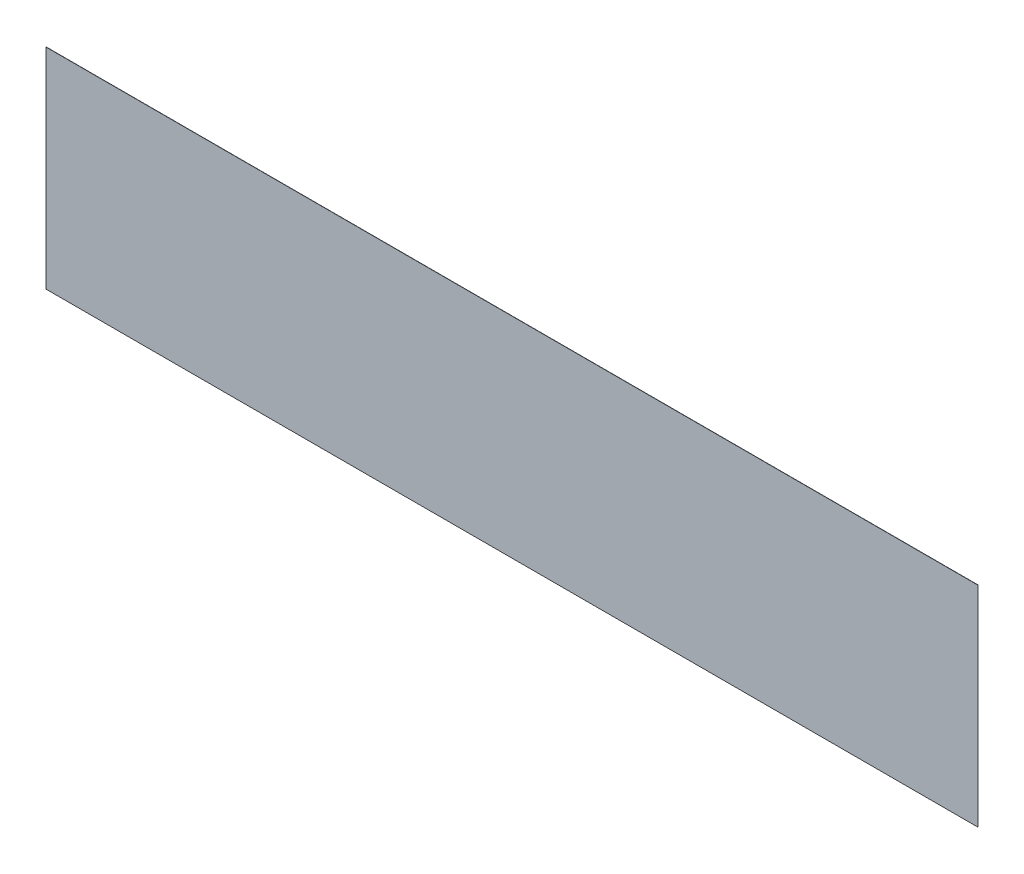
SolidWorks part; units mm, degrees
ref_plane "Front Plane" through (0, 0, 0) normal (0, 0, 1) x (1, 0, 0)
ref_plane "Top Plane" through (0, 0, 0) normal (0, 1, 0) x (1, 0, 0)
ref_plane "Right Plane" through (0, 0, 0) normal (1, 0, 0) x (0, 0, -1)
sketch "Sketch1" plane through (0, 0, 0) normal (0, 0, 1) x (1, 0, 0)
  line L1 (-20, -4.5) -> (20, -4.5)
  line L2 (-20, -4.5) -> (-20, 4.5)
  line L3 (-20, 4.5) -> (20, 4.5)
  line L4 (20, -4.5) -> (20, 4.5)
  line L5 (-20, -4.5) -> (20, 4.5) construction
  line L6 (-20, 4.5) -> (20, -4.5) construction
  point P0 (0, 0)
  dimension "D1" = 9
  dimension "D2" = 40
extrude "Boss-Extrude1" add sketch "Sketch1" along normal blind 0.01
